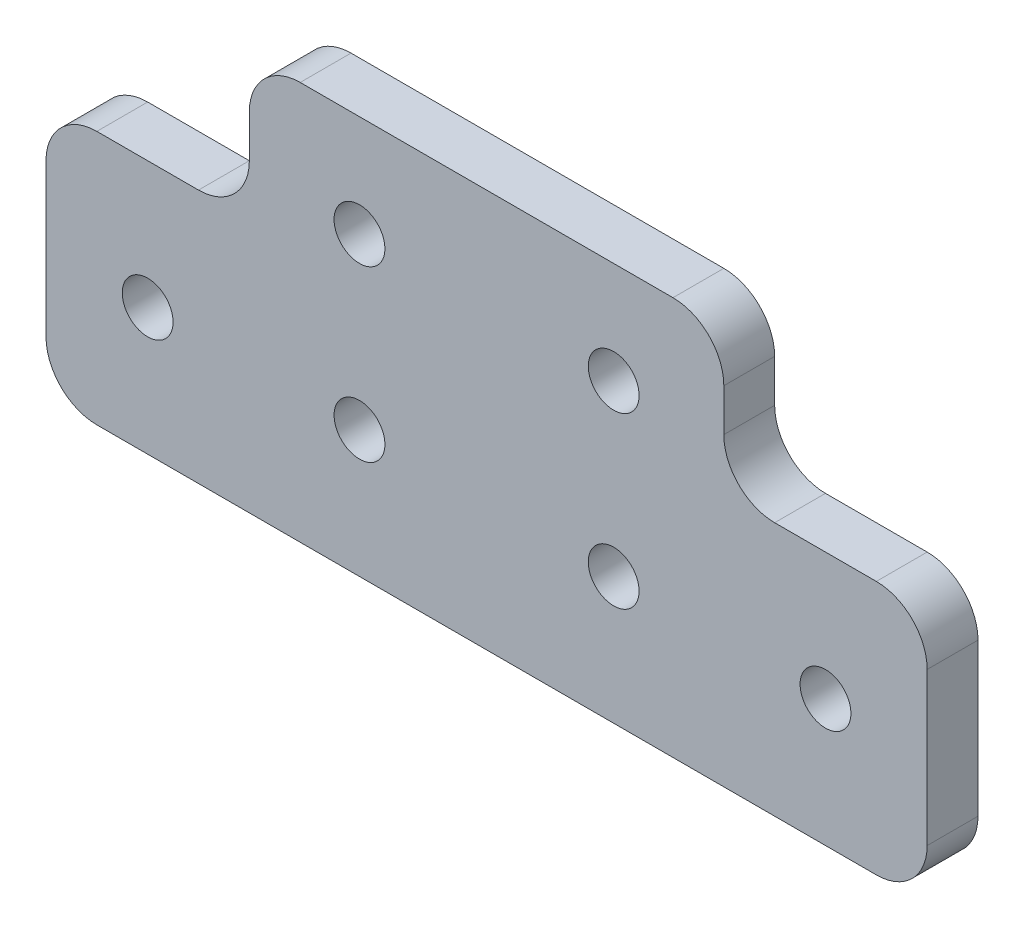
SolidWorks part; units mm, degrees
ref_plane "前视基准面" through (0, 0, 0) normal (0, 0, 1) x (1, 0, 0)
ref_plane "上视基准面" through (0, 0, 0) normal (0, 1, 0) x (1, 0, 0)
ref_plane "右视基准面" through (0, 0, 0) normal (1, 0, 0) x (0, 0, -1)
other "Configuration Table"
sketch "草图1" plane through (0, 0, 0) normal (0, 0, 1) x (1, 0, 0)
  line L0 (-49.6069, 0) -> (49.6069, 0) construction
  line L1 (0, -42.0552) -> (0, 42.0552) construction
  line L2 (-14, 11) -> (14, 11)
  line L3 (14, 11) -> (14, -11)
  line L4 (-14, -11) -> (14, -11)
  line L5 (-14, 11) -> (-14, -11)
  circle A0 centre (7.5, 5) radius 1.5
  circle A1 centre (7.5, -5) radius 1.5
  circle A2 centre (-7.5, -5) radius 1.5
  circle A3 centre (-7.5, 5) radius 1.5
  point P3 (-14, 0)
  point P13 (14, 0)
  point P15 (0, 0)
  point P20 (0, -11)
  point P21 (0, 11)
  dimension "D1" = 3
  dimension "D2" = 10
  dimension "D3" = 15
  dimension "D4" = 28
  dimension "D5" = 22
extrude "凸台-拉伸1" add sketch "草图1" along normal blind 3
sketch "草图2" plane through (0, 0, 3) normal (0, 0, 1) x (1, 0, 0)
  line L0 (7.5, -5) -> (30.0763, -5) construction
  line L1 (-26, 2.5) -> (26, 2.5)
  line L2 (26, 2.5) -> (26, -12.5)
  line L3 (26, -12.5) -> (-26, -12.5)
  line L4 (-26, -12.5) -> (-26, 2.5)
  line L5 (0, 0) -> (0, 17.266) construction
  circle A0 centre (20, -5) radius 1.5
  circle A1 centre (-20, -5) radius 1.5
  circle A2 centre (-7.5, -5) radius 1.5 construction
  circle A3 centre (7.5, -5) radius 1.5 construction
  circle A4 centre (-7.5, -5) radius 1.5
  circle A5 centre (7.5, -5) radius 1.5
  dimension "D2" = 3
  dimension "D1" = 15
  dimension "D3" = 20
  dimension "D4" = 26
extrude "凸台-拉伸3" add sketch "草图2" against normal blind 3
fillet "圆角1" radius 3 8 edges at (26, -12.5, 1.5) (-26, -12.5, 1.5) (-26, 2.5, 1.5) (-14, 2.5, 1.5) (14, 2.5, 1.5) (26, 2.5, 1.5) (14, 11, 1.5) (-14, 11, 1.5)
